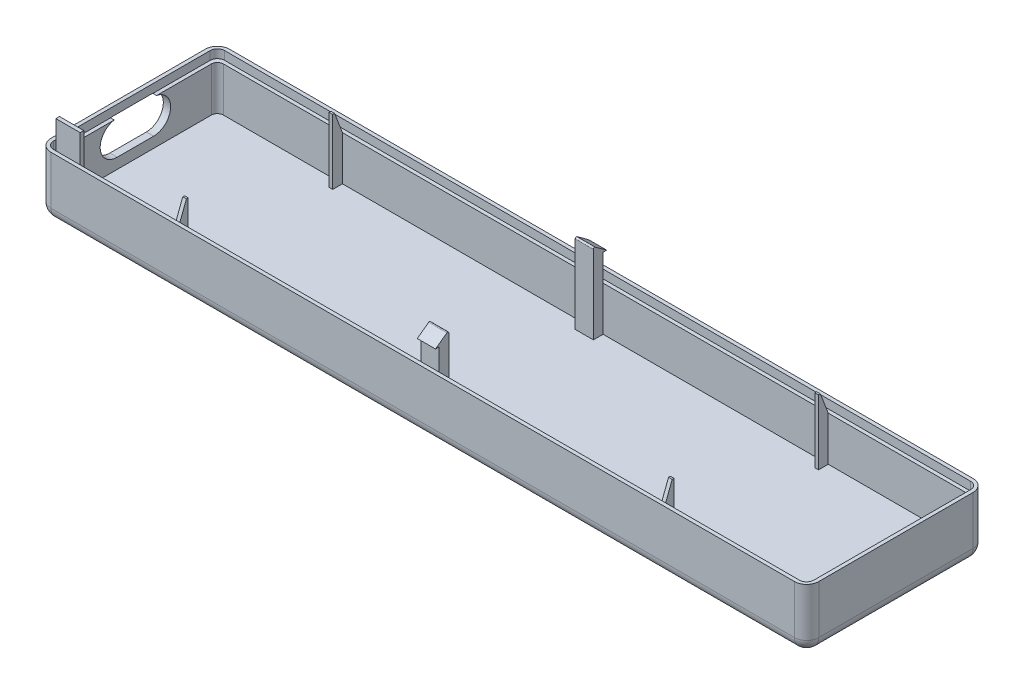
SolidWorks part; units mm, degrees
ref_plane "Front Plane" through (0, 0, 0) normal (0, 0, 1) x (1, 0, 0)
ref_plane "Top Plane" through (0, 0, 0) normal (0, 1, 0) x (1, 0, 0)
ref_plane "Right Plane" through (0, 0, 0) normal (1, 0, 0) x (0, 0, -1)
sketch "Sketch1" plane through (0, 0, 0) normal (0, 1, 0) x (1, 0, 0)
  line L1 (-80.2894, -18.669) -> (80.2894, -18.669)
  line L2 (-80.2894, -18.669) -> (-80.2894, 18.669)
  line L3 (-80.2894, 18.669) -> (80.2894, 18.669)
  line L4 (80.2894, -18.669) -> (80.2894, 18.669)
  line L5 (-80.2894, -18.669) -> (80.2894, 18.669) construction
  line L6 (-80.2894, 18.669) -> (80.2894, -18.669) construction
  point P0 (0, 0)
  dimension "D1" = 160.5788
  dimension "D2" = 37.338
extrude "Boss-Extrude1" add sketch "Sketch1" along normal blind 12.7
sketch "Sketch2" plane through (0, 12.7, 0) normal (0, 1, 0) x (1, 0, 0)
  line L0 (-80.2894, 18.669) -> (-80.2894, -18.669) construction
  line L1 (-78.7654, 17.145) -> (78.7654, 17.145)
  line L2 (-78.7654, 17.145) -> (-78.7654, -17.145)
  line L3 (-78.7654, -17.145) -> (78.7654, -17.145)
  line L4 (78.7654, 17.145) -> (78.7654, -17.145)
  line L5 (-78.7654, 17.145) -> (78.7654, -17.145) construction
  line L6 (-78.7654, -17.145) -> (78.7654, 17.145) construction
  line L7 (-80.2894, -18.669) -> (80.2894, -18.669) construction
  point P0 (0, 0)
  dimension "D1" = 1.524
  dimension "D2" = 1.524
extrude "Cut-Extrude3" cut sketch "Sketch2" against normal offset from surface (11.049 mm away) 1.651 up to face at (0, 0, 0)
fillet "Fillet1" radius 2.54 8 edges at (80.2894, 0, 0) (80.2894, 6.35, -18.669) (0, 0, -18.669) (0, 0, 18.669) (-80.2894, 0, 0) (-80.2894, 6.35, -18.669) (-80.2894, 6.35, 18.669) (80.2894, 6.35, 18.669)
fillet "Fillet2" radius 1.27 4 edges at (78.7654, 7.1755, -17.145) (78.7654, 7.1755, 17.145) (-78.7654, 7.1755, -17.145) (-78.7654, 7.1755, 17.145)
sketch "Sketch3" plane through (-80.2894, 0, 0) normal (-1, 0, 0) x (0, 0, 1)
  line L0 (3.81, 7.4193) -> (-3.81, 7.4193) construction
  line L1 (3.81, 3.8633) -> (-3.81, 3.8633)
  line L2 (3.81, 10.9753) -> (-3.81, 10.9753)
  line L3 (-16.129, 12.7) -> (16.129, 12.7) construction
  line L4 (0, 12.7) -> (0, -3.1618) construction
  arc A0 (3.81, 3.8633) -> (3.81, 10.9753) centre (3.81, 7.4193) ccw
  arc A1 (-3.81, 10.9753) -> (-3.81, 3.8633) centre (-3.81, 7.4193) ccw
  point P2 (0, 7.4193)
  dimension "D1" = 3.556
  dimension "D2" = 7.62
  dimension "D3" = 1.7247
extrude "Cut-Extrude4" cut sketch "Sketch3" against normal up to next
sketch "Sketch4" plane through (0, 12.7, 0) normal (0, 1, 0) x (1, 0, 0)
  line L0 (-80.2894, 16.129) -> (-80.2894, -16.129) construction
  line L1 (-79.5274, -17.907) -> (79.5274, -17.907)
  line L2 (-79.5274, -17.907) -> (-79.5274, 17.907)
  line L3 (-79.5274, 17.907) -> (79.5274, 17.907)
  line L4 (79.5274, -17.907) -> (79.5274, 17.907)
  line L5 (77.7494, 18.669) -> (-77.7494, 18.669) construction
  line L6 (80.2894, -16.129) -> (80.2894, 16.129) construction
  line L7 (-77.7494, -18.669) -> (77.7494, -18.669) construction
  dimension "D1" = 0.762
  dimension "D2" = 0.762
  dimension "D3" = 0.762
  dimension "D4" = 0.762
extrude "Cut-Extrude5" cut sketch "Sketch4" against normal blind 1.778
fillet "Fillet3" radius 1.524 4 edges at (79.5274, 11.811, -17.907) (-79.5274, 11.811, -17.907) (-79.5274, 11.811, 17.907) (79.5274, 11.811, 17.907)
sketch "Sketch5" plane through (0, 10.922, 0) normal (0, 1, 0) x (1, 0, 0)
  line L0 (-78.0034, -17.907) -> (78.0034, -17.907) construction
  line L1 (-72.4154, -17.907) -> (-77.4954, -17.907)
  line L2 (-72.4154, -17.907) -> (-72.4154, -17.145)
  line L3 (-72.4154, -17.145) -> (-77.4954, -17.145)
  line L4 (-77.4954, -17.907) -> (-77.4954, -17.145)
  line L5 (-77.4954, -17.145) -> (77.4954, -17.145) construction
  dimension "D1" = 5.08
extrude "Boss-Extrude2" add sketch "Sketch5" along normal blind 7.62
sketch "Sketch6" plane through (0, 1.651, 0) normal (0, 1, 0) x (1, 0, 0)
  line L0 (77.4954, 17.145) -> (-77.4954, 17.145) construction
  line L1 (-53.3654, 17.145) -> (-52.6034, 17.145)
  line L2 (-53.3654, 17.145) -> (-53.3654, 15.113)
  line L3 (-53.3654, 15.113) -> (-52.6034, 15.113)
  line L4 (-52.6034, 17.145) -> (-52.6034, 15.113)
  line L5 (-78.7654, 15.875) -> (-78.7654, -15.875) construction
  dimension "D1" = 0.762
  dimension "D2" = 2.032
  dimension "D3" = 25.4
extrude "Boss-Extrude3" add sketch "Sketch6" along normal offset from surface (13.589 mm away) 2.54 up to face at (-14.9911, 12.7, 3.5814) offset beyond the face yes
pattern_linear "LPattern1" count 2 spacing 101.6 along (1, 0, 0) count 2 spacing 32.258 along (0, 0, 1) of "Boss-Extrude3"
sketch "Sketch7" plane through (48.9966, 0, 0) normal (1, 0, 0) x (0, 0, -1)
  line L0 (17.145, 10.922) -> (15.494, 15.24)
  line L1 (17.145, 15.24) -> (15.113, 15.24) construction
  line L2 (15.494, 15.24) -> (17.145, 15.24)
  line L3 (17.145, 15.24) -> (17.145, 10.922)
  dimension "D1" = 0.381
extrude "Cut-Extrude6" cut sketch "Sketch7" against normal up to surface (102.362 mm away) up to face at (-53.3654, 8.9408, -16.3322)
mirror "Mirror1" about plane through (0, 0, 0) normal (0, 0, 1) of "Cut-Extrude6"
sketch "Sketch8" plane through (0, 1.651, 0) normal (0, 1, 0) x (1, 0, 0)
  line L0 (0, 0) -> (0, 21.7842) construction
  line L1 (1.905, -17.145) -> (-1.905, -17.145)
  line L2 (1.905, -17.145) -> (1.905, -15.113)
  line L3 (1.905, -15.113) -> (-1.905, -15.113)
  line L4 (-1.905, -17.145) -> (-1.905, -15.113)
  line L5 (1.905, 15.113) -> (-1.905, 15.113)
  line L6 (1.905, 15.113) -> (1.905, 17.145)
  line L7 (1.905, 17.145) -> (-1.905, 17.145)
  line L8 (-1.905, 15.113) -> (-1.905, 17.145)
  line L9 (-52.6034, -17.145) -> (48.2346, -17.145) construction
  line L10 (48.2346, 17.145) -> (-52.6034, 17.145) construction
  dimension "D1" = 3.81
  dimension "D2" = 2.032
extrude "Boss-Extrude4" add sketch "Sketch8" along normal offset from surface (14.859 mm away) 3.81 up to face at (-14.9911, 12.7, 3.5814) offset beyond the face yes
sketch "Sketch9" plane through (1.905, 0, 0) normal (1, 0, 0) x (0, 0, -1)
  line L0 (-15.113, 16.51) -> (-17.907, 16.51)
  line L1 (-17.907, 16.51) -> (-15.113, 18.542)
  line L2 (-15.113, 18.542) -> (-15.113, 16.51)
  line L3 (-17.145, 16.51) -> (-17.145, 10.922) construction
  dimension "D1" = 0.762
  dimension "D2" = 2.032
extrude "Boss-Extrude9" add sketch "Sketch9" against normal blind 3.81
fillet "Fillet4" radius 0.254 1 edges at (0, 18.542, 15.113)
mirror "Mirror2" about plane through (0, 0, 0) normal (0, 0, 1) of "Fillet4", "Boss-Extrude9"
